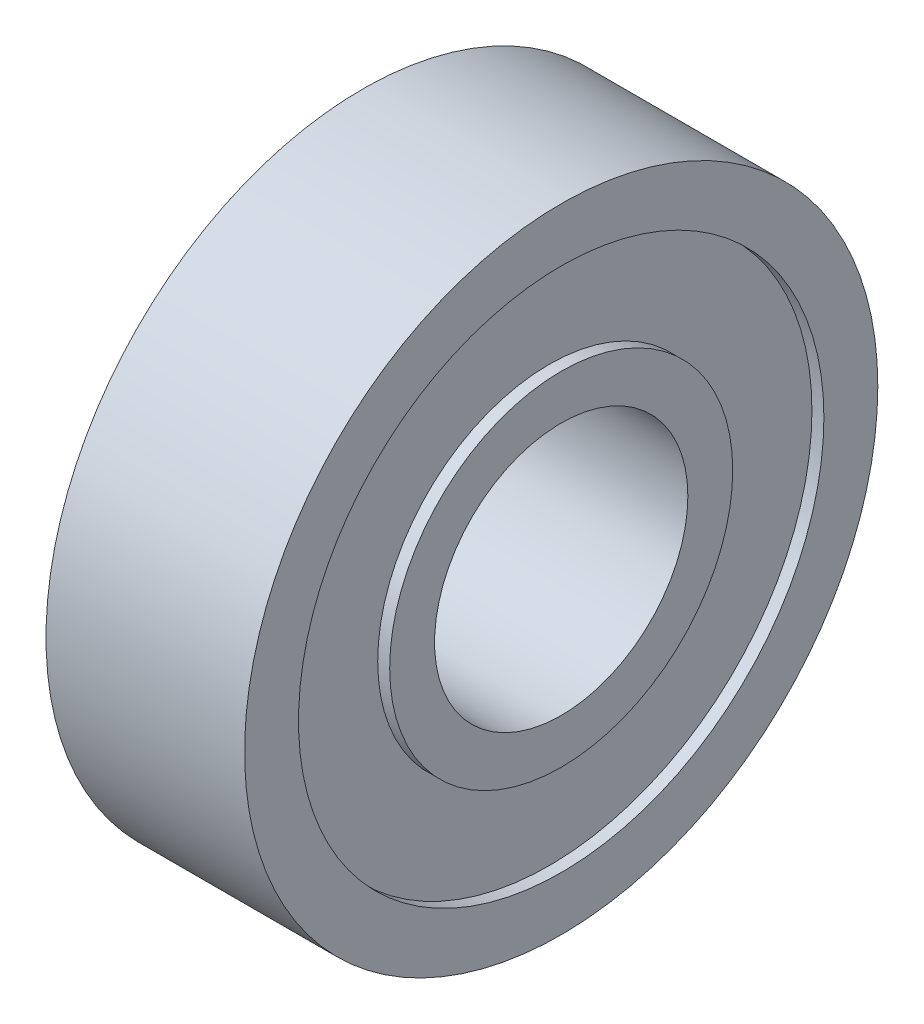
SolidWorks part; units mm, degrees
material "Plain Carbon Steel"
ref_plane "Front Plane" through (0, 0, 0) normal (0, 0, 1) x (1, 0, 0)
ref_plane "Top Plane" through (0, 0, 0) normal (0, 1, 0) x (1, 0, 0)
ref_plane "Right Plane" through (0, 0, 0) normal (1, 0, 0) x (0, 0, -1)
sketch "Sketch1" plane through (0, 0, 0) normal (0, 0, 1) x (1, 0, 0)
  line L0 (2.4892, 3.175) -> (-2.4892, 3.175)
  line L1 (-2.4892, 3.175) -> (-2.4892, 4.3)
  line L2 (-2.4892, 4.3) -> (-2.1892, 4.3)
  line L3 (-2.1892, 4.3) -> (-2.1892, 6.586)
  line L4 (-2.1892, 6.586) -> (-2.4892, 6.586)
  line L5 (-2.4892, 6.586) -> (-2.4892, 7.9375)
  line L6 (-2.4892, 7.9375) -> (2.4892, 7.9375)
  line L7 (0, 7.9375) -> (0, 3.175) construction
  line L8 (2.4892, 6.586) -> (2.4892, 7.9375)
  line L9 (2.1892, 6.586) -> (2.4892, 6.586)
  line L10 (2.1892, 4.3) -> (2.1892, 6.586)
  line L11 (2.4892, 4.3) -> (2.1892, 4.3)
  line L12 (2.4892, 3.175) -> (2.4892, 4.3)
  line L13 (0, 0) -> (-4.3663, 0) construction
  dimension "D1" = 6.35
  dimension "D2" = 15.875
  dimension "D3" = 4.9784
  dimension "D4" = 8.6
  dimension "D5" = 2.286
  dimension "D6" = 0.3
revolve "Revolve1" add sketch "Sketch1" angle 360 about L13
move or copy body "Body-Move/Copy1" [suppressed] bodies to move or copy 101
